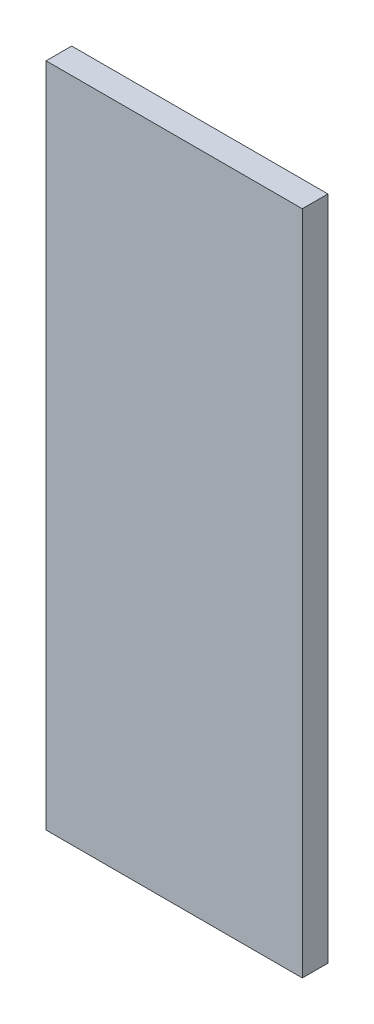
SolidWorks part; units mm, degrees
ref_plane "Front Plane" through (0, 0, 0) normal (0, 0, 1) x (1, 0, 0)
ref_plane "Top Plane" through (0, 0, 0) normal (0, 1, 0) x (1, 0, 0)
ref_plane "Right Plane" through (0, 0, 0) normal (1, 0, 0) x (0, 0, -1)
sketch "Sketch1" plane through (0, 0, 0) normal (0, 0, 1) x (1, 0, 0)
  line L1 (-25, -65) -> (25, -65)
  line L2 (-25, -65) -> (-25, 65)
  line L3 (-25, 65) -> (25, 65)
  line L4 (25, -65) -> (25, 65)
  line L5 (-25, -65) -> (25, 65) construction
  line L6 (-25, 65) -> (25, -65) construction
  point P1 (0, 0)
extrude "Boss-Extrude2" add sketch "Sketch1" along normal blind 5
